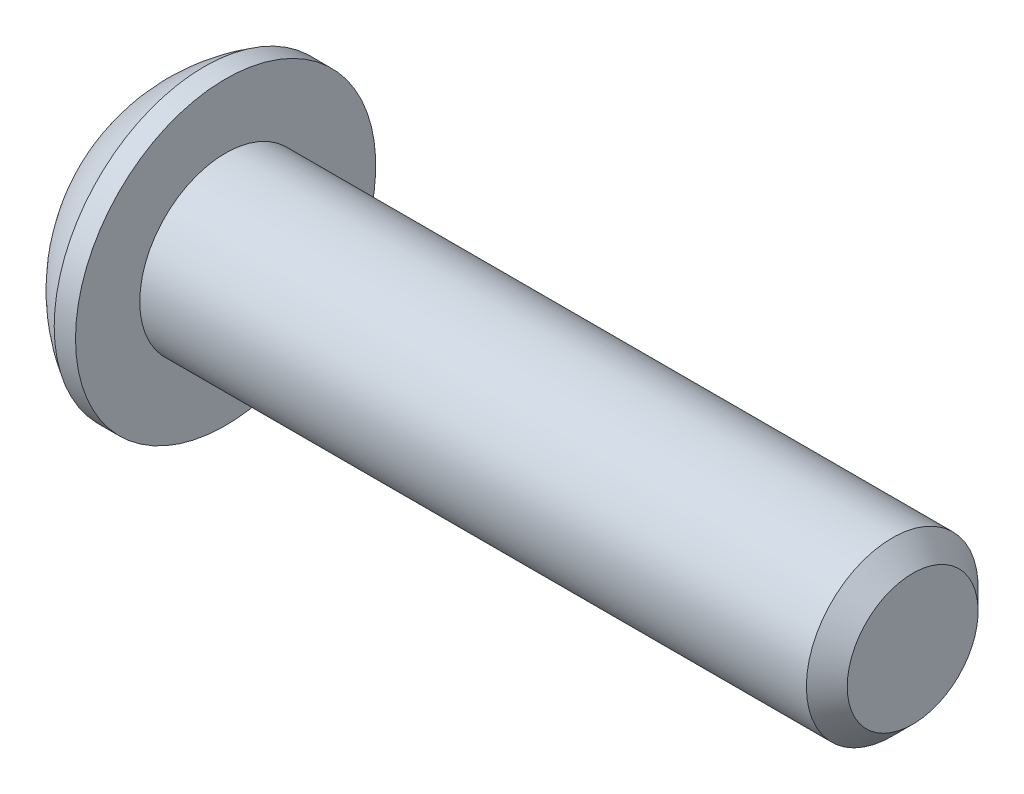
SolidWorks part; units mm, degrees
ref_plane "Plane1" through (0, 0, 0) normal (0, 0, 1) x (1, 0, 0)
ref_plane "Plane2" through (0, 0, 0) normal (0, 1, 0) x (1, 0, 0)
ref_plane "Plane3" through (0, 0, 0) normal (1, 0, 0) x (0, 0, -1)
sketch "BodySke" plane through (0, 0, 0) normal (0, 0, 1) x (1, 0, 0)
  line L0 (28.7528, 0) -> (28.7528, 2.4193)
  line L1 (27.9972, 3.175) -> (3.3528, 3.175)
  line L2 (3.3528, 3.175) -> (3.3528, 5.5499)
  line L3 (3.3528, 5.5499) -> (2.5654, 5.5499)
  line L4 (0, 0) -> (101.6, 0) construction
  line L5 (3.3528, -5.5499) -> (2.5654, -5.5499) construction
  line L6 (55.6768, -3.175) -> (3.3528, -3.175) construction
  line L7 (28.7528, 0) -> (0, 0)
  line L8 (0, 2.775) -> (0, -2.775) construction
  line L9 (0, 0) -> (0, 2.775)
  line L10 (28.7528, 2.4193) -> (27.9972, 3.175)
  line L11 (28.7528, -2.4193) -> (27.9972, -3.175) construction
  line L12 (4.6228, 9.525) -> (4.6228, -3.175) construction
  line L13 (3.3528, 9.525) -> (3.3528, -3.175) construction
  arc A1 (0, 2.775) -> (2.5654, 5.5499) centre (5.7851, 0) cw
  dimension "Diameter" = 6.35
  dimension "Length" = 25.4
  dimension "Head_dia" = 11.0998
  dimension "D1" = 5.5499
  dimension "Head_ht" = 3.3528
  dimension "Head_side_ht" = 0.7874
  dimension "Minor_dia" = 4.8387
  dimension "Body_ch_ang" = 45
  dimension "Advance" = 1.27
  dimension "Thread_nom" = 25.4
revolve "BaseBody" add sketch "BodySke" angle 360 about L4
cosmetic thread "ThreadCosmetic" [suppressed] parameters "Thread_length"=24.13, "Thread_minor"=4.8387
sketch "Sketch2" plane through (0, 0, 0) normal (0, 0, 1) x (1, 0, 0)
  line L0 (0, 1.9812) -> (2.2098, 1.9812)
  line L1 (2.2098, 1.9812) -> (3.3536, 0)
  line L3 (3.3536, 0) -> (0, 0)
  line L4 (0, 0) -> (0, 1.9812)
  line L5 (0, -1.9812) -> (2.2098, -1.9812) construction
  line L6 (0, 0) -> (47.625, 0) construction
  dimension "D2" = 60
  dimension "PreBroach_depth" = 2.2098
  dimension "PreBroach_dia" = 3.9624
revolve "PreBroach" cut sketch "Sketch2" angle 360 about L6
sketch "Sketch3" plane through (0, 0, 0) normal (1, 0, 0) x (0, 0, -1)
  line L0 (-1.9812, -1.1438) -> (-1.9812, 1.1438)
  line L1 (-1.9812, 1.1438) -> (0, 2.2877)
  line L2 (0, 2.2877) -> (1.9812, 1.1438)
  line L3 (1.9812, 1.1438) -> (1.9812, -1.1438)
  line L4 (1.9812, -1.1438) -> (0, -2.2877)
  line L5 (0, -2.2877) -> (-1.9812, -1.1438)
  dimension "Hex_size" = 3.9624
  dimension "D3" = 3.9624
  dimension "D1" = 1.9812
  dimension "D2" = 1.9812
extrude "Hex" cut sketch "Sketch3" along normal blind 2.2098
sketch "Sketch4" plane through (0, 9.525, 0) normal (1, 0, 0) x (0, 0, -1)
  line L0 (0, -9.525) -> (2.3876, -9.525)
  line L1 (0, -9.525) -> (6.1484, -5.9752) construction
  line L2 (0, -9.525) -> (1.1938, -7.4573)
  line L3 (1.9883, -8.949) -> (2.2704, -8.7861)
  line L4 (1.493, -8.0911) -> (1.7751, -7.9282)
  arc A0 (1.9883, -8.949) -> (1.493, -8.0911) centre (0, -9.525) ccw
  arc A1 (2.3876, -9.525) -> (2.2704, -8.7861) centre (0, -9.525) ccw
  arc A2 (1.1938, -7.4573) -> (1.7751, -7.9282) centre (0, -9.525) cw
  dimension "Spline_n_dim" = 4.1402
  dimension "Spline_m_dim" = 4.7752
  dimension "D1" = 30
  dimension "D2" = 60
  dimension "Spline_p_dim" = 0.9906
  dimension "D3" = 0.4953
extrude "Spline" [suppressed] cut sketch "Sketch4" along normal blind 2.2098
pattern_circular "CirPattern1" [suppressed] count 6 every 60 about axis through (0, 0, 0) along (1, 0, 0)
sketch "ThdSchSke" plane through (0, 0, 0) normal (0, 0, 1) x (1, 0, 0)
  line L0 (4.6228, -2.4193) -> (4.0937, -3.175)
  line L1 (4.6228, -2.4193) -> (5.1519, -3.175)
  line L2 (5.1519, -3.175) -> (5.1519, -3.9688)
  line L3 (-3.175, 0) -> (5.1513, 0) construction
  line L5 (5.1519, -3.9688) -> (4.0937, -3.9688)
  line L6 (4.0937, -3.9688) -> (4.0937, -3.175)
  dimension "Diameter" = 6.35
  dimension "Thread_minor" = 4.8387
  dimension "SideAngle" = 55
  dimension "VeeAngle" = 70
  dimension "Overcut" = 7.9375
  dimension "Start" = 4.6228
revolve "ThreadSchematic" [suppressed] cut sketch "ThdSchSke" angle 360 about L3
pattern_linear "ThdSchPat" [suppressed]
equation "\"D1@BodySke\" = \"Head_dia@BodySke\" * .5"
equation "\"Thread_minor@ThreadCosmetic\" = \"Minor_dia@BodySke\""
equation "\"D1@Sketch3\" = \"Hex_size@Sketch3\" / 2"
equation "\"D2@Sketch3\" = \"D1@Sketch3\""
equation "\"D3@Sketch3\" = \"Hex_size@Sketch3\""
equation "\"D3@Sketch4\" = \"Spline_p_dim@Sketch4\" / 2"
equation "\"D1@Sketch4\" = \"D2@Sketch4\" / 2"
equation "\"Thread_length@ThreadCosmetic\" = ((sgn( (\"Length@BodySke\" - \"Advance@BodySke\" ) - \"Thread_nom@BodySke\" )-1)*( (\"Length@BodySke\" - \"Advance@BodySke\" ) - \"Thread_nom@BodySke\" ))/-2+ \"Thread_nom@BodySke\""
equation "\"Thread_minor@ThdSchSke\" = \"Minor_dia@BodySke\""
equation "\"Diameter@ThdSchSke\" = \"Diameter@BodySke\""
equation "\"Overcut@ThdSchSke\" = \"Diameter@BodySke\" * 1.25"
equation "\"Start@ThdSchSke\" = \"Head_ht@BodySke\" + \"Length@BodySke\" - \"Thread_length@ThreadCosmetic\"  '---Non-countersunk---"
equation "\"Num_threads@ThdSchPat\" = int( \"Thread_length@ThreadCosmetic\" / \"Advance@BodySke\" + 0.999 )  + 1"
equation "\"Advance@ThdSchPat\" = \"Thread_length@ThreadCosmetic\" /  (\"Num_threads@ThdSchPat\" - 1) 'relax it"
equation "\"Num_threads@ThdSchPat\" = \"Num_threads@ThdSchPat\" - sgn( \"Num_threads@ThdSchPat\" - 1) '---chamfered tips only---"
